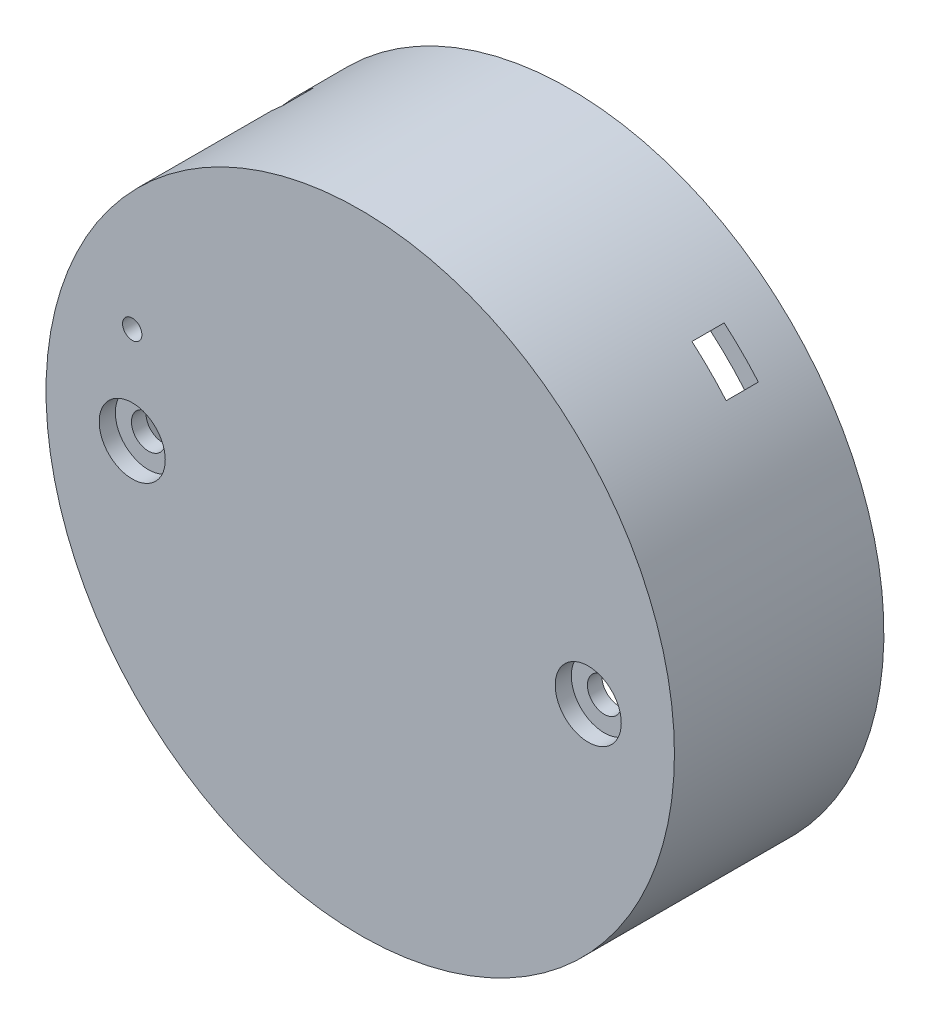
SolidWorks part; units mm, degrees
ref_plane "前视基准面" through (0, 0, 0) normal (0, 0, 1) x (1, 0, 0)
ref_plane "上视基准面" through (0, 0, 0) normal (0, 1, 0) x (1, 0, 0)
ref_plane "右视基准面" through (0, 0, 0) normal (1, 0, 0) x (0, 0, -1)
other "Configuration Table"
sketch "草图1" plane through (0, 0, 0) normal (0, 0, 1) x (1, 0, 0)
  line L0 (-4.9697, -5.3068) -> (15.3903, -5.3068) construction
  line L1 (-1.7897, -9.462) -> (12.2103, -9.462) construction
  line L2 (5.2103, 9.538) -> (5.2103, -5.6737) construction
  line L3 (5.2103, -5.6737) -> (5.2103, -9.462) construction
  line L4 (-20.5262, 27.538) -> (29.3458, 27.538) construction
  arc A1 (15.3903, -5.3068) -> (-4.9697, -5.3068) centre (5.2103, 9.538) ccw construction
  circle A2 centre (5.2103, 9.538) radius 18 construction
  circle A3 centre (5.2103, 9.538) radius 19.5 construction
  spline S0 degree 2 poles (-4.9697, -5.3068) (-1.8954, -6.8939) (-1.7897, -9.462) knots 0 0 0 0.933514 0.933514 0.933514 construction
  spline S1 degree 2 poles (15.3903, -5.3068) (12.316, -6.8939) (12.2103, -9.462) knots 0 0 0 0.933514 0.933514 0.933514 construction
  point P7 (5.2103, -9.462)
  dimension "D1" = 20.36
  dimension "D2" = 36
  dimension "D6" = 39
  dimension "D3" = 19
  dimension "D4" = 14
  dimension "D5" = 37
sketch "草图2" plane through (0, 0, 0) normal (0, 0, 1) x (1, 0, 0)
  circle A0 centre (5.2103, 9.538) radius 19.5
  circle A1 centre (5.2103, 9.538) radius 19.5 construction
extrude "凸台-拉伸1" add sketch "草图2" along normal blind 13
sketch "草图3" plane through (0, 0, 0) normal (0, 0, 1) x (1, 0, 0)
  arc A1 (-2.0895, -9.4744) -> (12.51, -9.4744) centre (5.2103, 9.538) ccw
  arc A2 (15.5443, -5.5649) -> (-5.1238, -5.5649) centre (5.2103, 9.538) ccw
  arc A3 (15.5443, -5.5649) -> (-5.1238, -5.5649) centre (5.2103, 9.538) ccw
  spline S0 degree 3 poles (229.8671, -2977.6257) (427.1916, -179.0998) (-8.4928, -35.7015) (35.8591, 22.0661) (561.3621, -75.3509) (2726.8544, -1276.7174) knots -21.363862 -21.363862 -21.363862 -21.363862 0.5 0.5 23.131712 23.131712 23.131712 23.131712 only from (12.51, -9.4744) to (15.5443, -5.5649)
  spline S1 degree 3 poles (-2716.4543, -1276.7288) (-550.9449, -75.3515) (-25.4386, 22.0662) (18.9132, -35.7012) (-416.7636, -179.0973) (-219.4516, -2977.5533) knots -22.131783 -22.131783 -22.131783 -22.131783 0.5 0.5 22.363674 22.363674 22.363674 22.363674 only from (-5.1238, -5.5649) to (-2.0895, -9.4744)
  spline S2 degree 3 poles (12.51, -9.4744) (12.5429, -8.6746) (12.8021, -7.9653) (13.7989, -6.667) (14.5427, -6.0797) (15.5443, -5.5649) knots 0 0 0 0 0.5 0.5 1 1 1 1
  spline S3 degree 3 poles (-5.1238, -5.5649) (-4.1222, -6.0797) (-3.3783, -6.667) (-2.3815, -7.9653) (-2.1224, -8.6746) (-2.0895, -9.4744) knots 0 0 0 0 0.5 0.5 1 1 1 1
  dimension "D1" = 0.3
extrude "切除-拉伸1" cut sketch "草图3" along normal blind 1.5
sketch "草图4" plane through (0, 0, 0) normal (0, 0, 1) x (1, 0, 0)
  circle A0 centre (5.2103, 9.538) radius 18.3
  arc A1 (15.5443, -5.5649) -> (-5.1238, -5.5649) centre (5.2103, 9.538) ccw construction
extrude "切除-拉伸2" cut sketch "草图4" along normal blind 11.1
sketch "草图5" plane through (0, 0, 0) normal (0, 0, 1) x (1, 0, 0)
  line L0 (15.2103, 22.538) -> (-4.7897, -3.462) construction
  line L1 (15.2103, 22.538) -> (-4.7897, 22.538) construction
  line L2 (15.2103, 22.538) -> (15.2103, -3.462) construction
  line L3 (15.2103, -3.462) -> (-4.7897, -3.462) construction
  line L4 (-4.7897, 22.538) -> (-4.7897, -3.462) construction
  line L5 (-4.7897, 22.538) -> (15.2103, -3.462) construction
  line L6 (15.2103, 9.538) -> (23.5103, 9.538) construction
  line L7 (-4.7897, 9.538) -> (-13.0897, 9.538) construction
  line L8 (-8.9397, 9.538) -> (-8.9397, 15.538) construction
  circle A0 centre (5.2103, 9.538) radius 18.3 construction
  circle A1 centre (19.3603, 9.538) radius 1.05
  circle A2 centre (-8.9397, 9.538) radius 1.05
  circle A3 centre (-8.9397, 15.538) radius 0.6
  point P4 (5.2103, 9.538)
  dimension "D3" = 2.1
  dimension "D4" = 2.1
  dimension "D6" = 1.2
  dimension "D1" = 20
  dimension "D2" = 26
  dimension "D5" = 6
extrude "切除-拉伸3" cut sketch "草图5" along normal through all
sketch "草图6" plane through (0, 0, 13) normal (0, 0, 1) x (1, 0, 0)
  circle A0 centre (-8.9397, 9.538) radius 2.05
  circle A1 centre (19.3603, 9.538) radius 2.05
  dimension "D1" = 4.1
extrude "切除-拉伸4" cut sketch "草图6" against normal blind 1
ref_plane "基准面1" through (0, 0, 3.1) normal (0, 0, -1) x (-1, 0, 0)
sketch "草图8" plane through (0, 0, 3.1) normal (0, 0, -1) x (-1, 0, 0)
  line L0 (-5.2103, 9.538) -> (-5.2103, -9.962) construction
  line L1 (-9.5853, -9.962) -> (-0.8353, -9.962)
  line L2 (-9.5853, -9.962) -> (-9.5853, -2.662)
  line L3 (-9.5853, -2.662) -> (-0.8353, -2.662)
  line L4 (-0.8353, -2.662) -> (-0.8353, -9.962)
  arc A0 (-12.6847, -8.4727) -> (2.2641, -8.4727) centre (-5.2103, 9.538) ccw construction
  point P8 (-5.2103, -9.962)
  dimension "D1" = 8.75
  dimension "D2" = 7.3
extrude "切除-拉伸5" cut sketch "草图8" against normal blind 3.25
sketch "草图9" plane through (0, 0, 3.1) normal (0, 0, -1) x (-1, 0, 0)
  line L0 (-5.2103, 9.538) -> (-20.0595, 24.3872) construction
  line L1 (-5.2103, 9.538) -> (9.639, 24.3872) construction
  line L2 (-23.2103, 9.538) -> (12.7897, 9.538) construction
  line L3 (-21.1202, 23.3265) -> (-18.9989, 21.2052)
  line L4 (-18.9989, 25.4479) -> (-16.8775, 23.3265)
  line L5 (-18.9989, 25.4479) -> (-21.1202, 23.3265)
  line L6 (-16.8775, 23.3265) -> (-18.9989, 21.2052)
  line L7 (6.457, 23.3265) -> (8.5783, 21.2052)
  line L8 (8.5783, 25.4479) -> (10.6996, 23.3265)
  line L9 (8.5783, 25.4479) -> (6.457, 23.3265)
  line L10 (10.6996, 23.3265) -> (8.5783, 21.2052)
  circle A0 centre (-5.2103, 9.538) radius 18
  circle A1 centre (-5.2103, 9.538) radius 21
  point P12 (-20.0595, 24.3872)
  point P13 (0, 0)
  point P14 (-17.9382, 22.2659)
  point P21 (21.5742, 31.0565)
  point P22 (7.5176, 22.2659)
  point P23 (9.639, 24.3872)
  point P24 (0, 0)
  dimension "D1" = 36
  dimension "D2" = 3
  dimension "D3" = 45
  dimension "D4" = 45
  dimension "D5" = 3
  dimension "D6" = 3
  dimension "D7" = 3
extrude "切除-拉伸6" cut sketch "草图9" against normal blind 2 contours L4 A1 L3 L6 | L10 A1 L9 L7
